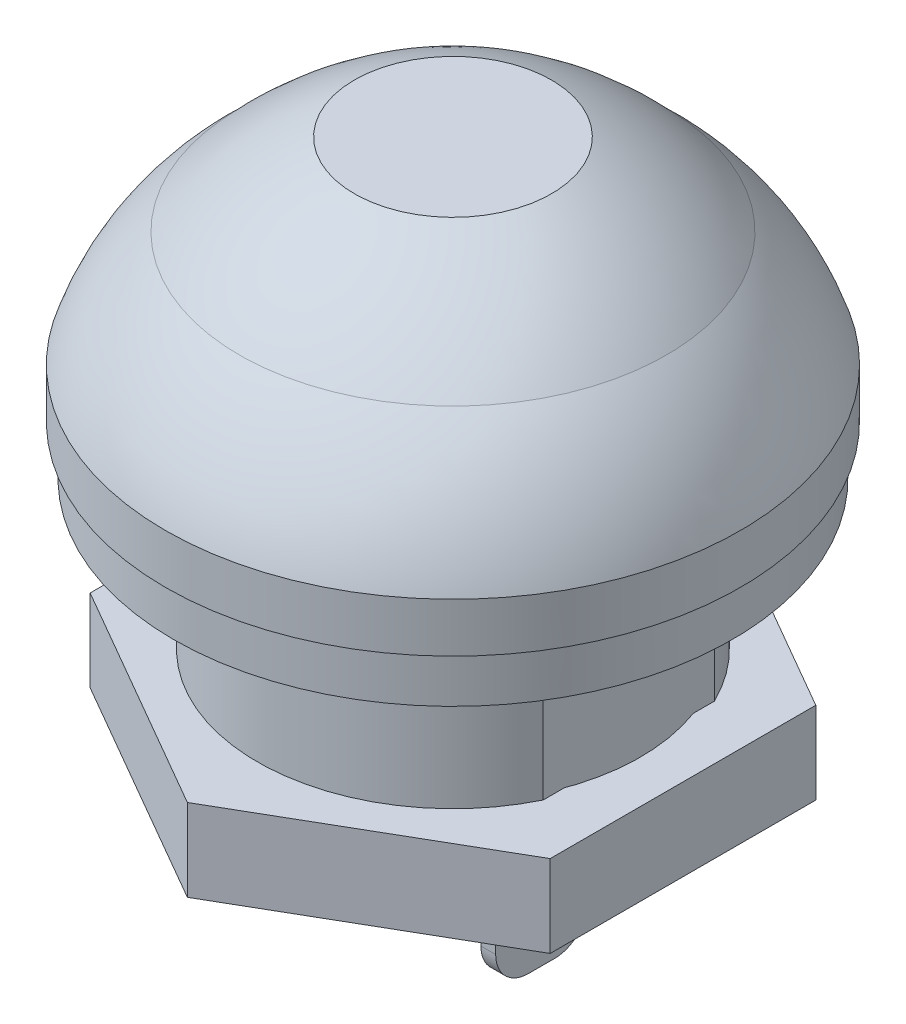
SolidWorks part; units mm, degrees
ref_plane "Front Plane" through (0, 0, 0) normal (0, 0, 1) x (1, 0, 0)
ref_plane "Top Plane" through (0, 0, 0) normal (0, 1, 0) x (1, 0, 0)
ref_plane "Right Plane" through (0, 0, 0) normal (1, 0, 0) x (0, 0, -1)
sketch "Sketch1" plane through (0, 0, 0) normal (0, 1, 0) x (1, 0, 0)
  line L0 (-5.35, 2.6038) -> (-5.35, -2.6038)
  line L1 (5.35, 2.6038) -> (5.35, -2.6038)
  line L2 (-5.35, 0) -> (0, 0) construction
  line L3 (0, 0) -> (5.35, 0) construction
  arc A0 (-5.35, -2.6038) -> (5.35, -2.6038) centre (0, 0) ccw
  arc A1 (5.35, 2.6038) -> (-5.35, 2.6038) centre (0, 0) ccw
  dimension "D2" = 5.95
  dimension "D1" = 10.7
extrude "Boss-Extrude1" add sketch "Sketch1" against normal blind 7
sketch "Sketch2" plane through (0, 0, 0) normal (0, 1, 0) x (1, 0, 0)
  line L0 (-2.755, -6.025) -> (2.755, -6.025)
  line L1 (0, 6.625) -> (0, 0) construction
  line L2 (0, 0) -> (0, -6.025) construction
  arc A0 (2.755, -6.025) -> (-2.755, -6.025) centre (0, 0) ccw
  dimension "D1" = 13.25
  dimension "D2" = 12.65
extrude "Boss-Extrude2" add sketch "Sketch2" along normal blind 1.5
sketch "Sketch3" plane through (0, 1.5, 0) normal (0, 1, 0) x (1, 0, 0)
  circle A0 centre (0, 0) radius 8.75
  dimension "D1" = 17.5
extrude "Boss-Extrude3" add sketch "Sketch3" along normal blind 1.5
sketch "Sketch4" plane through (0, 0, 0) normal (0, 0, 1) x (1, 0, 0)
  line L0 (0, 1.5) -> (0, 6.5)
  line L1 (-2.755, 1.5) -> (2.755, 1.5) construction
  line L2 (0, 6.5) -> (0, 9)
  line L3 (0, 6.5) -> (-6.5, 6.5) construction
  line L4 (0, 9) -> (-3, 9)
  line L5 (-8.75, 3) -> (-8.75, 1.5)
  line L6 (-8.75, 1.5) -> (0, 1.5)
  line L7 (-8.75, 3) -> (-1.1271, 0.5728)
  line L8 (0, 1.5) -> (0, -7) construction
  line L9 (-5.35, -7) -> (5.35, -7) construction
  arc A0 (-3, 9) -> (-6.5, 6.5) centre (0.9264, -0.1969) ccw
  arc A1 (-8.75, 3) -> (-6.5, 6.5) centre (-1.1271, 0.5728) cw
  dimension "D5" = 8
  dimension "D6" = 10
  dimension "D1" = 5
  dimension "D2" = 2.5
  dimension "D3" = 6.5
  dimension "D4" = 3
revolve "Revolve2" add sketch "Sketch4" angle 360 about L8
sketch "Sketch5" plane through (0, -7, 0) normal (0, -1, 0) x (1, 0, 0)
  circle A0 centre (0, 0) radius 5.0109
extrude "Boss-Extrude4" add sketch "Sketch5" along normal blind 1
sketch "Sketch6" plane through (0, -8, 0) normal (0, -1, 0) x (1, 0, 0)
  line L0 (-2.25, 0) -> (0, 0) construction
  line L1 (-2.7, 1.4) -> (-2.25, 1.4)
  line L2 (-2.7, 1.4) -> (-2.7, -1.4)
  line L3 (-2.7, -1.4) -> (-2.25, -1.4)
  line L4 (-2.25, 1.4) -> (-2.25, -1.4)
  line L5 (0, 0) -> (0, 6.025) construction
  line L6 (-2.755, 6.025) -> (2.755, 6.025) construction
  line L7 (2.25, 1.4) -> (2.25, -1.4)
  line L8 (2.7, -1.4) -> (2.25, -1.4)
  line L9 (2.7, 1.4) -> (2.7, -1.4)
  line L10 (2.7, 1.4) -> (2.25, 1.4)
  dimension "D1" = 2.8
  dimension "D2" = 0.45
  dimension "D3" = 4.5
extrude "Boss-Extrude5" add sketch "Sketch6" along normal blind 3.5
sketch "Sketch7" plane through (2.7, 0, 0) normal (1, 0, 0) x (0, 0, -1)
  line L0 (0, -9.35) -> (0, -10.15) construction
  line L1 (0.6, -9.35) -> (0.6, -10.15)
  line L2 (-0.6, -9.35) -> (-0.6, -10.15)
  line L3 (0, -8.75) -> (0, -9.35) construction
  line L4 (0, -10.15) -> (0, -10.75) construction
  line L5 (1.4, -11.5) -> (-1.4, -11.5) construction
  arc A0 (0.6, -9.35) -> (-0.6, -9.35) centre (0, -9.35) ccw
  arc A1 (-0.6, -10.15) -> (0.6, -10.15) centre (0, -10.15) ccw
  point P3 (0, -9.75)
  point P14 (0, -11.5)
  dimension "D1" = 1.2
  dimension "D2" = 2
  dimension "D3" = 0.75
extrude "Cut-Extrude1" cut sketch "Sketch7" against normal through all
fillet "Fillet1" radius 1 4 edges at (-2.475, -11.5, -1.4) (-2.475, -11.5, 1.4) (2.475, -11.5, -1.4) (2.475, -11.5, 1.4)
sketch "Sketch8" plane through (0, 1.5, 0) normal (0, -1, 0) x (1, 0, 0)
  circle A0 centre (0, 0) radius 8.5
  circle A1 centre (0, 0) radius 7
  dimension "D1" = 17
  dimension "D2" = 14
extrude "Boss-Extrude6" add sketch "Sketch8" along normal blind 1.5
sketch "Sketch9" plane through (0, -7, 0) normal (0, -1, 0) x (1, 0, 0)
  line L0 (0, 0) -> (0, -8.0829) construction
  line L1 (0, -8.0829) -> (7, -4.0415)
  line L2 (7, -4.0415) -> (7, 4.0415)
  line L3 (7, 4.0415) -> (0, 8.0829)
  line L4 (0, 8.0829) -> (-7, 4.0415)
  line L5 (-7, 4.0415) -> (-7, -4.0415)
  line L6 (-7, -4.0415) -> (0, -8.0829)
  circle A0 centre (0, 0) radius 7 construction
  circle A1 centre (0, 0) radius 5.7
  dimension "D2" = 11.4
  dimension "D1" = 14
extrude "Boss-Extrude7" add sketch "Sketch9" against normal blind 2.5 separate body
